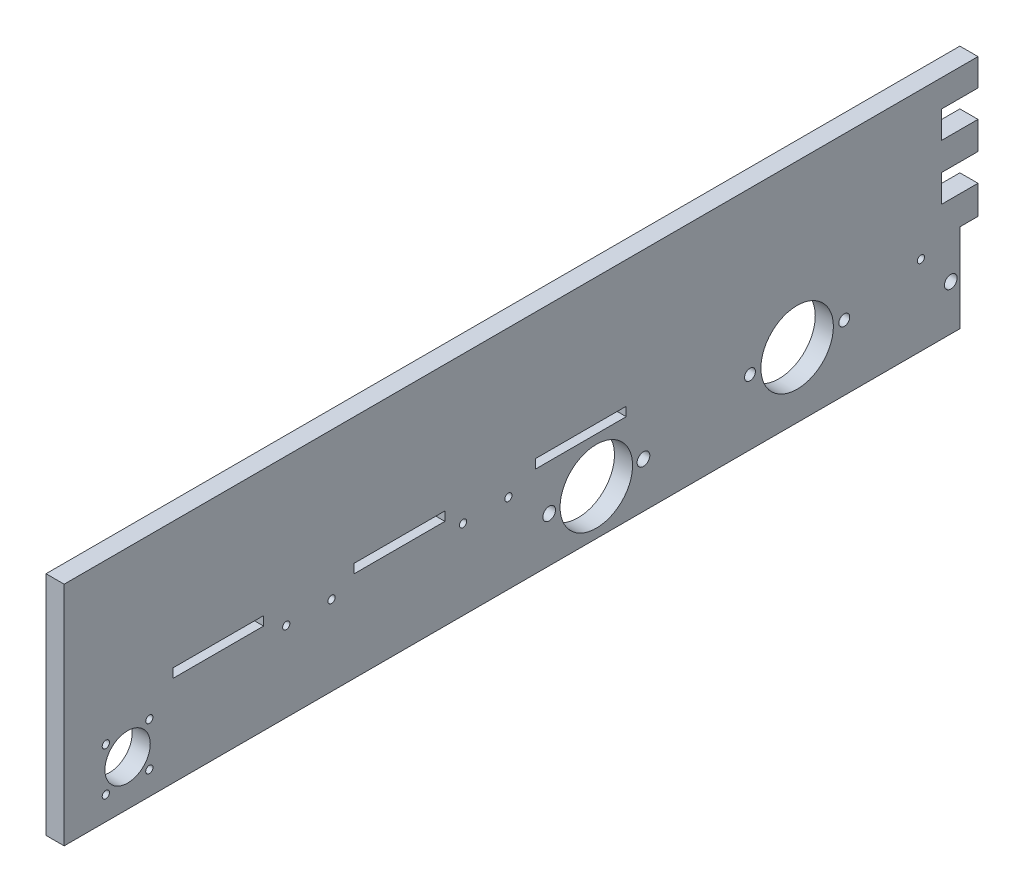
SolidWorks part; units mm, degrees
ref_plane "정면" through (0, 0, 0) normal (0, 0, 1) x (1, 0, 0)
ref_plane "윗면" through (0, 0, 0) normal (0, 1, 0) x (1, 0, 0)
ref_plane "우측면" through (0, 0, 0) normal (1, 0, 0) x (0, 0, -1)
sketch "스케치1" plane through (0, 0, 0) normal (1, 0, 0) x (0, 0, -1)
  line L0 (-325, 0) -> (325, 0) construction
  line L1 (325, 0) -> (591.861, 180) construction
  line L6 (-339, -14) -> (-311, -14) construction
  line L15 (-339, 14) -> (-311, 14) construction
  line L16 (-339, 14) -> (-339, -14) construction
  line L18 (-311, 14) -> (-311, -14) construction
  line L19 (-350, -25) -> (353.4809, -25)
  line L20 (311, 14) -> (311, -14) construction
  line L21 (339, 14) -> (339, -14) construction
  line L22 (339, 14) -> (311, 14) construction
  line L23 (339, -14) -> (311, -14) construction
  line L24 (-350, -25) -> (-350, 30)
  line L25 (300, 25) -> (350, 25) construction
  line L26 (-300, 25) -> (-350, 25) construction
  line L27 (-300, 25) -> (-300, -25) construction
  line L28 (300, 25) -> (300, -25) construction
  line L31 (365.2669, -21.1583) -> (609.4584, 155.7033)
  line L32 (580.4109, 207.729) -> (150, 30)
  line L34 (350, 25) -> (350, -25) construction
  line L35 (46, 52.6531) -> (46, -51.2062) construction
  line L36 (150, 37.2232) -> (150, -42.9076) construction
  line L39 (-350, 30) -> (150, 30)
  circle A0 centre (-325, 0) radius 12.5 construction
  circle A2 centre (-337, -12) radius 2 construction
  circle A3 centre (-313, -12) radius 2 construction
  circle A4 centre (-313, 12) radius 2 construction
  circle A5 centre (-337, 12) radius 2 construction
  circle A6 centre (337, 12) radius 2 construction
  circle A7 centre (313, 12) radius 2 construction
  circle A8 centre (313, -12) radius 2 construction
  circle A9 centre (337, -12) radius 2 construction
  circle A10 centre (325, 0) radius 12.5 construction
  circle A11 centre (0, 0) radius 7.5 construction
  circle A12 centre (0, 0) radius 20 construction
  circle A13 centre (-26, 0) radius 3.5 construction
  circle A14 centre (26, 0) radius 3.5 construction
  circle A15 centre (591.861, 180) radius 7.5 construction
  circle A16 centre (570.306, 165.461) radius 3.5 construction
  circle A17 centre (613.416, 194.539) radius 3.5 construction
  circle A18 centre (591.861, 180) radius 20 construction
  arc A24 (365.2669, -21.1583) -> (353.4809, -25) centre (353.4809, -5) cw
  arc A26 (580.4109, 207.729) -> (609.4584, 155.7033) centre (594.9347, 181.7161) cw
  point P3 (0, 0)
  dimension "D6" = 20
  dimension "D5" = 50
  dimension "D1" = 55
  dimension "D2" = 146
  dimension "D3" = 650
  dimension "D4" = 180
  dimension "D7" = 26
  dimension "D8" = 944.9347
extrude "보스-돌출2" add sketch "스케치1" along normal blind 10
sketch "스케치3" plane through (10, 0, 0) normal (1, 0, 0) x (0, 0, -1)
  circle A0 centre (613.416, 194.539) radius 3.5 construction
  circle A1 centre (570.306, 165.461) radius 3.5 construction
  circle A2 centre (591.861, 180) radius 20 construction
  circle A3 centre (337, -12) radius 2 construction
  circle A4 centre (313, 12) radius 2 construction
  circle A5 centre (313, -12) radius 2 construction
  circle A6 centre (337, 12) radius 2 construction
  circle A7 centre (325, 0) radius 12.5 construction
  circle A8 centre (26, 0) radius 3.5 construction
  circle A9 centre (-26, 0) radius 3.5 construction
  circle A10 centre (0, 0) radius 20 construction
  circle A11 centre (-313, -12) radius 2 construction
  circle A12 centre (-313, 12) radius 2 construction
  circle A13 centre (-325, 0) radius 12.5 construction
  circle A14 centre (-337, -12) radius 2 construction
  circle A15 centre (-337, 12) radius 2 construction
  circle A16 centre (613.416, 194.539) radius 3.5
  circle A17 centre (570.306, 165.461) radius 3.5
  circle A18 centre (591.861, 180) radius 20
  circle A19 centre (337, -12) radius 2
  circle A20 centre (313, 12) radius 2
  circle A21 centre (313, -12) radius 2
  circle A22 centre (337, 12) radius 2
  circle A23 centre (325, 0) radius 12.5
  circle A24 centre (26, 0) radius 3.5
  circle A25 centre (-26, 0) radius 3.5
  circle A26 centre (0, 0) radius 20
  circle A27 centre (-313, -12) radius 2
  circle A28 centre (-313, 12) radius 2
  circle A29 centre (-325, 0) radius 12.5
  circle A30 centre (-337, -12) radius 2
  circle A31 centre (-337, 12) radius 2
extrude "컷-돌출1" cut sketch "스케치3" against normal through all contours A29 | A27 | A30 | A31 | A28 | A23 | A20 | A21 | A19 | A22 | A18 | A16 | A17
sketch "스케치4" plane through (10, 0, 0) normal (1, 0, 0) x (0, 0, -1)
  line L2 (100, 25) -> (100, 30)
  line L4 (-50, 25) -> (-100, 25)
  line L6 (100, 25) -> (50, 25)
  line L7 (50, 25) -> (50, 30)
  line L8 (300, 25) -> (300, 30)
  line L9 (300, 30) -> (250, 30)
  line L10 (250, 30) -> (250, 25)
  line L11 (250, 25) -> (300, 25)
  line L13 (150, 30) -> (200, 30)
  line L14 (200, 30) -> (200, 25)
  line L15 (200, 25) -> (150, 25)
  line L16 (150, 25) -> (150, 30)
  line L17 (-100, 25) -> (-100, 30)
  line L19 (-50, 25) -> (-50, 30)
  line L21 (-300, 30) -> (-300, 35)
  line L24 (-300, 25) -> (-300, 30)
  line L25 (-300, 25) -> (-250, 25)
  line L26 (-250, 25) -> (-250, 30)
  line L28 (-200, 25) -> (-200, 30)
  line L29 (-200, 25) -> (-150, 25)
  line L30 (-150, 25) -> (-150, 30)
  line L32 (-250, 30) -> (-250, 35)
  line L33 (-150, 30) -> (-150, 35)
  line L34 (-200, 30) -> (-200, 35)
  line L35 (-100, 30) -> (-100, 35)
  line L36 (-50, 30) -> (-50, 35)
  line L37 (100, 30) -> (100, 35)
  line L38 (50, 30) -> (50, 35)
  line L40 (100, 35) -> (50, 35)
  line L41 (-150, 35) -> (-200, 35)
  line L42 (-100, 35) -> (-50, 35)
  line L43 (-250, 35) -> (-300, 35)
  circle A8 centre (-237.5, 19) radius 2
  circle A9 centre (-212.5, 19) radius 2
  circle A10 centre (-139.9962, 19) radius 2
  circle A11 centre (-114.9962, 19) radius 2
  circle A12 centre (112.5, 19) radius 2
  circle A13 centre (137.5, 19) radius 2
  circle A14 centre (212.5, 19) radius 2
  circle A15 centre (237.5, 19) radius 2
sketch "스케치6" plane through (0, 30, 0) normal (0, 1, 0) x (1, 0, 0)
  line L0 (10, -50) -> (10, -100)
  line L1 (0, 150) -> (0, -350) construction
  line L2 (10, -300) -> (10, -250)
  line L3 (0, 100) -> (0, 50)
  line L4 (10, -250) -> (10, -300) construction
  line L5 (10, -300) -> (10, -250) construction
  line L6 (10, -250) -> (0, -250)
  line L7 (10, -300) -> (0, -300)
  line L8 (10, -200) -> (10, -150)
  line L9 (10, -150) -> (10, -200) construction
  line L10 (10, -200) -> (10, -150) construction
  line L11 (10, -150) -> (0, -150)
  line L12 (10, -200) -> (0, -200)
  line L13 (10, -100) -> (0, -100)
  line L14 (10, -100) -> (10, -50) construction
  line L15 (10, -50) -> (10, -100) construction
  line L16 (10, -50) -> (0, -50)
  line L17 (0, -250) -> (0, -300)
  line L18 (10, 100) -> (10, 50)
  line L19 (10, 100) -> (10, 50) construction
  line L20 (10, 100) -> (10, 50) construction
  line L21 (10, 50) -> (0, 50)
  line L22 (10, 100) -> (0, 100)
  line L23 (0, -150) -> (0, -200)
  line L24 (0, -50) -> (0, -100)
extrude "컷-돌출14" cut sketch "스케치6" against normal blind 5
sketch "스케치7" plane through (10, 0, 0) normal (1, 0, 0) x (0, 0, -1)
  line L0 (155, 30) -> (200, 30)
  line L1 (200, 30) -> (200, 25)
  line L4 (250, 30) -> (250, 25)
  line L5 (250, 25) -> (300, 25)
  line L6 (300, 25) -> (300, 30)
  line L7 (300, 30) -> (250, 30)
  line L8 (155, 25) -> (200, 25)
  line L9 (200, 25) -> (150, 25) construction
  line L10 (155, 25) -> (155, 30)
extrude "컷-돌출17" cut sketch "스케치7" against normal through all
extrude "컷-돌출18" cut sketch "스케치4" against normal blind 10 contours A8 | A9 | A10 | A11 | A12 | A14 | A15
sketch "스케치8" plane through (0, 0, 350) normal (0, 0, 1) x (1, 0, 0)
  line L4 (0, 30) -> (0, -25)
  line L5 (0, -25) -> (10, -25)
  line L6 (10, -25) -> (10, 30)
  line L7 (10, 30) -> (0, 30)
  line L8 (0, 30) -> (0, -25)
  line L9 (0, -25) -> (10, -25)
  line L10 (10, -25) -> (10, 30)
  line L11 (10, 30) -> (0, 30)
  dimension "D1" = 0
extrude "보스-돌출3" add sketch "스케치8" along normal blind 10
sketch "스케치9" plane through (10, 0, 0) normal (1, 0, 0) x (0, 0, -1)
  circle A2 centre (-92.5, 0) radius 3.5
  circle A3 centre (-40.5, 0) radius 3.5
  circle A4 centre (-66.5, 0) radius 20
  circle A9 centre (155, 0) radius 20
  circle A10 centre (181, 0) radius 3.5
  circle A11 centre (129, 0) radius 3.5
extrude "컷-돌출19" cut sketch "스케치9" against normal through all
sketch "스케치10" plane through (0, 0, 0) normal (1, 0, 0) x (0, 0, -1)
  line L11 (100, 30) -> (100, 25)
  line L12 (100, 25) -> (50, 25)
  line L17 (50, 25) -> (50, 30)
  line L19 (-50, 100) -> (319.5208, 100)
  line L20 (580.4109, 207.729) -> (150, 30) construction
  line L21 (319.5208, 100) -> (150, 30)
  line L22 (150, 30) -> (100, 30)
  line L23 (50, 30) -> (-50, 30)
  line L24 (-50, 30) -> (-360, 30)
  line L25 (-360, 30) -> (-360, 100)
  line L26 (-360, 100) -> (-50, 100)
  point P12 (139.7616, 36.9837)
  point P13 (576.6226, 216.9837)
  dimension "D1" = 70
extrude "보스-돌출4" add sketch "스케치10" along normal blind 10
sketch "스케치14" plane through (10, 0, 0) normal (1, 0, 0) x (0, 0, -1)
  circle A3 centre (44.25, 11) radius 10 construction
  circle A4 centre (44.25, 11) radius 20
  circle A5 centre (70.25, 11) radius 3
  circle A7 centre (18.25, 11) radius 3
  point P0 (0, 0)
  dimension "D1" = 40
  dimension "D2" = 6
  dimension "D3" = 26
  dimension "D4" = 26
extrude "컷-돌출20" cut sketch "스케치14" against normal through all
sketch "스케치15" plane through (10, 0, 0) normal (1, 0, 0) x (0, 0, -1)
  line L0 (133.0091, 35.5821) -> (133.0091, 30.5821)
  line L7 (580.4109, 207.729) -> (319.5208, 100) construction
  circle A4 centre (331.4334, 50.824) radius 2
  circle A5 centre (316.195, 87.8077) radius 2
  circle A6 centre (451.6303, 100.3488) radius 2
  circle A7 centre (436.3919, 137.3324) radius 2
  point P1 (0, 0)
  point P3 (0, 0)
  point P24 (0, 0)
  point P26 (0, 0)
  dimension "D2" = 4
  dimension "D7" = 10
  dimension "D3" = 4
  dimension "D4" = 4
  dimension "D5" = 4
  dimension "D11" = 40
extrude "컷-돌출22" cut sketch "스케치15" against normal through all contours A5 | A4 | A7 | A6
sketch "스케치16" plane through (10, 0, 0) normal (1, 0, 0) x (0, 0, -1)
  line L0 (-11.5, 71.5023) -> (-11.5, -50.9694) construction
  line L1 (92.5, 71.5023) -> (92.5, -48.7682) construction
  circle A1 centre (-40.5, 0) radius 3.5 construction
  circle A5 centre (112.5, 19) radius 2 construction
  point P8 (92.5, 11.3671)
  dimension "D1" = 29
  dimension "D2" = 20
sketch "스케치17" plane through (10, 0, 0) normal (1, 0, 0) x (0, 0, -1)
  line L0 (319.5208, 100) -> (319.5208, -43.2034) construction
  line L4 (134, 100) -> (144, 100)
  line L6 (134, 114.9691) -> (134, -37.6192) construction
  line L7 (319.5208, 100) -> (-360, 100) construction
  line L17 (144, 114.9691) -> (144, -9.8458) construction
  line L19 (124, 114.9691) -> (124, -12.9668) construction
  line L20 (144, 100) -> (144, 85)
  line L21 (144, 85) -> (124, 85)
  line L22 (124, 85) -> (124, 70.0094)
  line L23 (124, 70.0094) -> (144, 70.0094)
  line L24 (144, 70.0094) -> (144, 54.646)
  line L25 (144, 54.646) -> (124, 54.646)
  line L26 (124, 54.646) -> (124, 39.4856)
  line L27 (124, 39.4856) -> (144, 39.4856)
  line L28 (144, 39.4856) -> (144, 23.6607)
  line L29 (144, 23.6607) -> (134, 23.6607)
  line L30 (134, 23.6607) -> (134, -25.2592)
  line L31 (134, -25.2592) -> (695.029, -25.2592)
  line L32 (695.029, -25.2592) -> (695.029, 260.6848)
  line L33 (695.029, 260.6848) -> (134, 260.6848)
  line L34 (134, 260.6848) -> (134, 100)
  dimension "D2" = 10
  dimension "D1" = 10
  dimension "D3" = 15
extrude "컷-돌출25" cut sketch "스케치17" against normal through all
